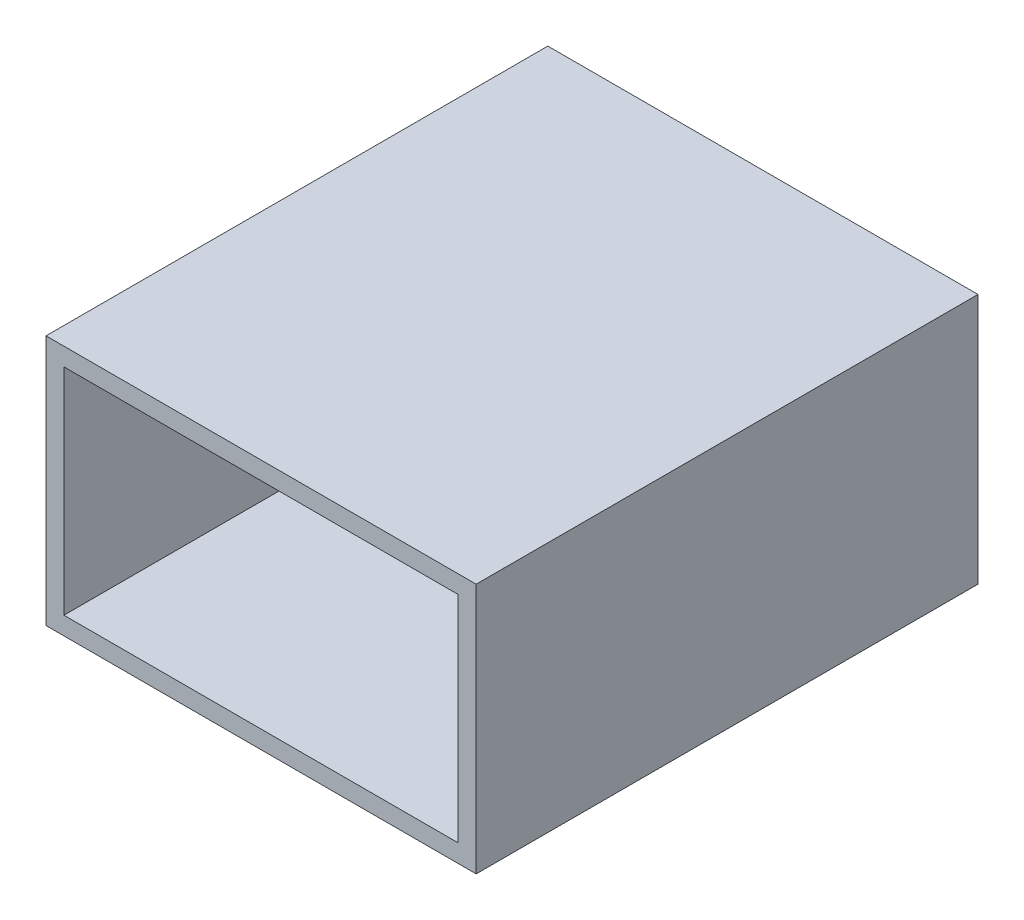
SolidWorks part; units mm, degrees
ref_plane "Front Plane" through (0, 0, 0) normal (0, 0, 1) x (1, 0, 0)
ref_plane "Top Plane" through (0, 0, 0) normal (0, 1, 0) x (1, 0, 0)
ref_plane "Right Plane" through (0, 0, 0) normal (1, 0, 0) x (0, 0, -1)
sketch "Sketch1" plane through (0, 0, 0) normal (0, 0, 1) x (1, 0, 0)
  line L0 (-8.5814, 3.907) -> (-8.5814, -8.093)
  line L1 (-9.5814, 4.907) -> (14.4186, 4.907)
  line L2 (-9.5814, 4.907) -> (-9.5814, -9.093)
  line L3 (-9.5814, -9.093) -> (14.4186, -9.093)
  line L4 (14.4186, 4.907) -> (14.4186, -9.093)
  line L5 (-8.5814, -8.093) -> (13.4186, -8.093)
  line L6 (13.4186, 3.907) -> (13.4186, -8.093)
  line L7 (13.4186, 3.907) -> (-8.5814, 3.907)
  dimension "D1" = 14
  dimension "D2" = 24
  dimension "D3" = 1
  dimension "D4" = 1
  dimension "D5" = 1
  dimension "D6" = 1
extrude "Boss-Extrude4" add sketch "Sketch1" against normal blind 28 contours L2 L1 L4 L3
sketch "Sketch3" plane through (0, 0, 0) normal (0, 0, 1) x (1, 0, 0)
  line L0 (-8.5814, 3.907) -> (13.4186, 3.907)
  line L1 (13.4186, 3.907) -> (13.4186, -8.093)
  line L2 (-8.5814, -8.093) -> (13.4186, -8.093)
  line L3 (-8.5814, 3.907) -> (-8.5814, -8.093)
  line L4 (-9.5814, 4.907) -> (14.4186, 4.907) construction
  line L5 (-9.5814, 4.907) -> (-9.5814, -9.093) construction
  line L6 (-9.5814, -9.093) -> (14.4186, -9.093) construction
  line L7 (14.4186, 4.907) -> (14.4186, -9.093) construction
  dimension "D1" = 1
  dimension "D2" = 1
  dimension "D3" = 1
  dimension "D4" = 1
extrude "Cut-Extrude1" cut sketch "Sketch3" against normal blind 27 contours L1 L2 L3 L0
sketch "Sketch4" plane through (-9.5814, 0, 0) normal (-1, 0, 0) x (0, 0, 1)
  circle A0 centre (-21, -2.093) radius 6
  circle A1 centre (-13.5, -2.093) radius 2.4879
extrude "Cut-Extrude7" cut sketch "Sketch4" against normal blind 5 contours A0 A1 | A1 A0 | A0 A1
